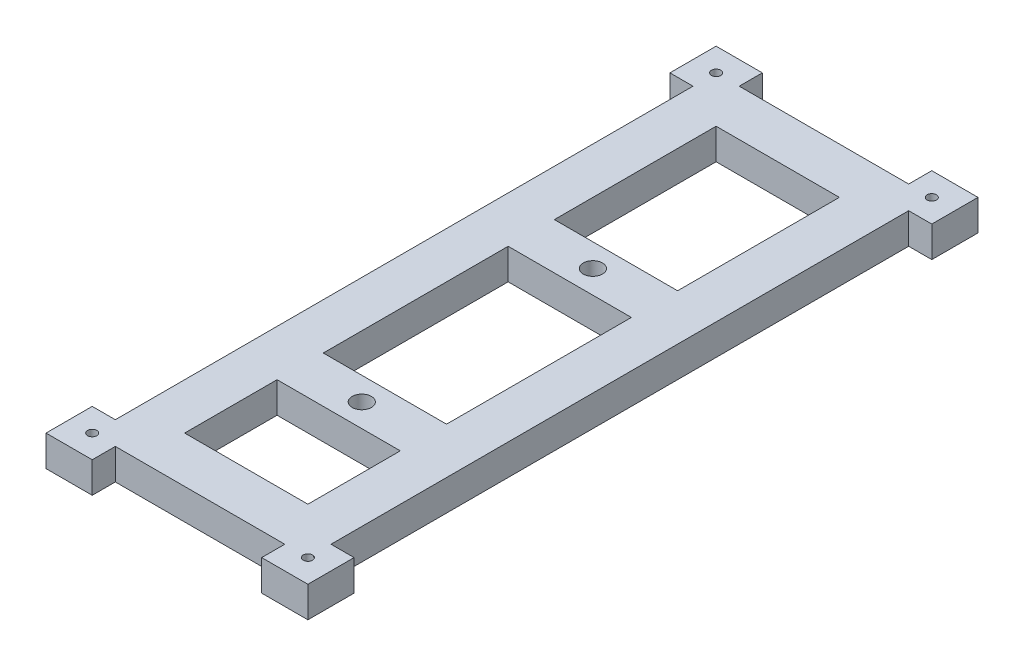
SolidWorks part; units mm, degrees
ref_plane "前视基准面" through (0, 0, 0) normal (0, 0, 1) x (1, 0, 0)
ref_plane "上视基准面" through (0, 0, 0) normal (0, 1, 0) x (1, 0, 0)
ref_plane "右视基准面" through (0, 0, 0) normal (1, 0, 0) x (0, 0, -1)
other "Configuration Table"
sketch "草图1" plane through (0, 0, 0) normal (0, 1, 0) x (1, 0, 0)
  line L1 (0, 0) -> (34, 0)
  line L2 (0, 0) -> (0, -87)
  line L3 (0, -87) -> (34, -87)
  line L4 (34, 0) -> (34, -87)
  circle A2 centre (3, -3) radius 0.6
  circle A3 centre (31, -3) radius 0.6
  circle A4 centre (31, -84) radius 0.6
  circle A5 centre (3, -84) radius 0.6
  dimension "D3" = 3
  dimension "D6" = 3
  dimension "D7" = 1.2
  dimension "D1" = 87
  dimension "D2" = 34
  dimension "D4" = 3
  dimension "D5" = 3
extrude "凸台-拉伸1" add sketch "草图1" along normal blind 4
sketch "草图2" plane through (0, 4, 0) normal (0, 1, 0) x (1, 0, 0)
  line L1 (0, 0) -> (6, 0)
  line L2 (0, 0) -> (0, -6)
  line L3 (0, -6) -> (6, -6)
  line L4 (6, 0) -> (6, -6)
  line L5 (34, 0) -> (28, 0)
  line L6 (34, 0) -> (34, -6)
  line L7 (34, -6) -> (28, -6)
  line L8 (28, 0) -> (28, -6)
  line L9 (34, -87) -> (28, -87)
  line L10 (34, -87) -> (34, -81)
  line L11 (34, -81) -> (28, -81)
  line L12 (28, -87) -> (28, -81)
  line L13 (0, -87) -> (6, -87)
  line L14 (0, -87) -> (0, -81)
  line L15 (0, -81) -> (6, -81)
  line L16 (6, -87) -> (6, -81)
  line L17 (3, -6) -> (31, -6)
  line L18 (3, -6) -> (3, -81)
  line L19 (3, -81) -> (31, -81)
  line L20 (31, -6) -> (31, -81)
  line L21 (6, -3) -> (28, -3)
  line L22 (6, -3) -> (6, -6)
  line L23 (6, -6) -> (28, -6)
  line L24 (28, -3) -> (28, -6)
  line L25 (28, -81) -> (6, -81)
  line L26 (28, -81) -> (28, -84)
  line L27 (28, -84) -> (6, -84)
  line L28 (6, -81) -> (6, -84)
  line L29 (0, 0) -> (0, -87) construction
  line L30 (34, 0) -> (34, -87) construction
  line L31 (0, 0) -> (34, 0) construction
  line L32 (17, -3) -> (17, -33)
  line L33 (9, -9) -> (25, -9)
  line L34 (9, -9) -> (9, -78)
  line L35 (9, -78) -> (25, -78)
  line L36 (25, -9) -> (25, -78)
  line L37 (17, -63) -> (17, -84)
  line L38 (12.5997, -60) -> (12.5997, -66) construction
  line L39 (9, -30) -> (25, -30)
  line L40 (9, -30) -> (9, -36)
  line L41 (9, -36) -> (25, -36)
  line L42 (25, -30) -> (25, -36)
  line L43 (9, -60) -> (25, -60)
  line L44 (9, -60) -> (9, -66)
  line L45 (9, -66) -> (25, -66)
  line L46 (25, -60) -> (25, -66)
  line L47 (12.5997, -63) -> (17, -63) construction
  line L48 (13.0568, -30) -> (13.0568, -36) construction
  line L49 (13.0568, -36) -> (13.0568, -33)
  line L50 (13.0568, -33) -> (17, -33) construction
  circle A0 centre (17, -33) radius 1.25
  circle A1 centre (17, -63) radius 1.25
  dimension "D11" = 2.5
  dimension "D1" = 6
  dimension "D2" = 3
  dimension "D3" = 3
  dimension "D4" = 3
  dimension "D5" = 3
  dimension "D6" = 3
  dimension "D7" = 6
  dimension "D8" = 6
  dimension "D9" = 3
  dimension "D10" = 30
  dimension "D12" = 6
  dimension "D13" = 6
  dimension "D14" = 30
extrude "切除-拉伸1" cut sketch "草图2" against normal through all
sketch "草图3" plane through (0, 0, 0) normal (0, -1, 0) x (1, 0, 0)
  circle A0 centre (17, 63) radius 1.75
  circle A1 centre (17, 33) radius 1.75
  dimension "D1" = 3.5
extrude "切除-拉伸2" cut sketch "草图3" against normal blind 2 contours A0 | A1
